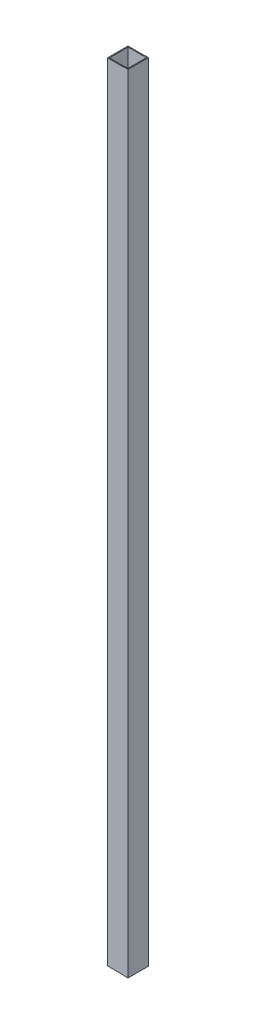
SolidWorks part; units mm, degrees
ref_plane "Front Plane" through (0, 0, 0) normal (0, 0, 1) x (1, 0, 0)
ref_plane "Top Plane" through (0, 0, 0) normal (0, 1, 0) x (1, 0, 0)
ref_plane "Right Plane" through (0, 0, 0) normal (1, 0, 0) x (0, 0, -1)
sketch "Sketch1" plane through (0, 0, 0) normal (0, 1, 0) x (1, 0, 0)
  line L0 (0, 0) -> (0, 50)
  line L1 (0, 50) -> (50, 50)
  line L2 (50, 50) -> (50, 0)
  line L3 (50, 0) -> (0, 0)
  line L4 (2.2, 47.8) -> (47.8, 47.8)
  line L5 (47.8, 47.8) -> (47.8, 2.2)
  line L6 (47.8, 2.2) -> (2.2, 2.2)
  line L7 (2.2, 2.2) -> (2.2, 47.8)
  dimension "D1" = 50
  dimension "D2" = 50
  dimension "D3" = 2.2
extrude "Boss-Extrude1" add sketch "Sketch1" along normal blind 1923
sketch "Sketch2" plane through (0, 0, 0) normal (0, 0, 1) x (1, 0, 0)
  line L0 (0, 0) -> (0, 0.5)
  line L1 (0, 1923) -> (0, 0) construction
  line L2 (0, 0.5) -> (40, 0.5)
  line L3 (40, 0.5) -> (40, 0)
  line L5 (40, 0) -> (0, 0)
  line L6 (0, 1923) -> (40, 1923)
  line L7 (0, 1923) -> (50, 1923) construction
  line L8 (40, 1923) -> (40, 1922.5)
  line L9 (40, 1922.5) -> (0, 1922.5)
  line L10 (0, 1922.5) -> (0, 1923)
  dimension "D1" = 0.5
  dimension "D2" = 40
  dimension "D3" = 0.5
  dimension "D4" = 40
extrude "Cut-Extrude2" cut sketch "Sketch2" against normal blind 50
equation "\"SquareTube_length\"=1923.0"
equation "\"D1@Boss-Extrude1\"=\"SquareTube_length\""
equation "\"SquareTube_inFront1_cutDepth50_R\"=0.5"
equation "\"D1@Sketch2\" = \"SquareTube_inFront4_cutDepth50_R\""
equation "\"SquareTube_inFront1_cutDepth50_L\"=0.5"
equation "\"D3@Sketch2\"= \"SquareTube_inFront4_cutDepth50_L\""
equation "\"CarBeamWidth\"=700.0"
equation "\"MetalSheet_3mm_length\"=5030.0"
equation "\"MetalSheet_3mm_width\"=1923.0"
equation "\"MetalSheet_3mm_FloorCut_L_length\"=1764.0"
equation "\"MetalSheet_3mm_FloorCut_L_disdance\"=1665.0"
equation "\"MetalSheet_3mm_FloorCut_R_length\"=1764.0"
equation "\"MetalSheet_3mm_FloorCut_R_disdance\"=1665.0"
equation "\"indoorHeight\"=1940.0"
equation "\"x\"=66.0"
equation "\"da\"=62.0"
equation "\"SquareTube_wheel_length\"= 750"
equation "\"channelSteel_length\"=5030.0"
equation "\"SquareTube_inFront2_cutDepth50_R\"=0.5"
equation "\"SquareTube_inFront2_cutDepth50_L\"=0.5"
equation "\"SquareTube_inFront3_cutDepth50_R\"=0.5"
equation "\"SquareTube_inFront3_cutDepth50_L\"=0.5"
equation "\"SquareTube_inFront4_cutDepth50_R\"=0.5"
equation "\"SquareTube_inFront4_cutDepth50_L\"=0.5"
equation "\"SquareTube_inFront5_cutDepth50_R\"=50"
equation "\"SquareTube_inFront5_cutDepth50_L\"=50"
equation "\"SquareTube_inFront6_cutDepth50_R\"=50"
equation "\"SquareTube_inFront6_cutDepth50_L\"=50"
equation "\"SquareTube_inFront7_cutDepth50_R\"=50"
equation "\"SquareTube_inFront7_cutDepth50_L\"=50"
equation "\"SquareTube_inFront8_cutDepth50_R\"=50"
equation "\"SquareTube_inFront8_cutDepth50_L\"=50"
equation "\"SquareTube_inFront9_cutDepth50_R\"=50"
equation "\"SquareTube_inFront9_cutDepth50_L\"=50"
equation "\"SquareTube_inFront10_cutDepth50_R\"=50"
equation "\"SquareTube_inFront10_cutDepth50_L\"=50"
equation "\"SquareTube_inBack1_cutDepth50_R\"=50"
equation "\"SquareTube_inBack1_cutDepth50_L\"=50"
equation "\"SquareTube_inBack2_cutDepth50_R\"=50"
equation "\"SquareTube_inBack2_cutDepth50_L\"=50"
equation "\"SquareTube_inBack3_cutDepth50_R\"=50"
equation "\"SquareTube_inBack3_cutDepth50_L\"=50"
equation "\"SquareTube_inBack4_cutDepth50_R\"=50"
equation "\"SquareTube_inBack4_cutDepth50_L\"=50"
equation "\"SquareTube_inBack5_cutDepth50_R\"=50"
equation "\"SquareTube_inBack5_cutDepth50_L\"=50"
equation "\"SquareTube_inBack6_cutDepth50_R\"=0.5"
equation "\"SquareTube_inBack6_cutDepth50_L\"=0.5"
